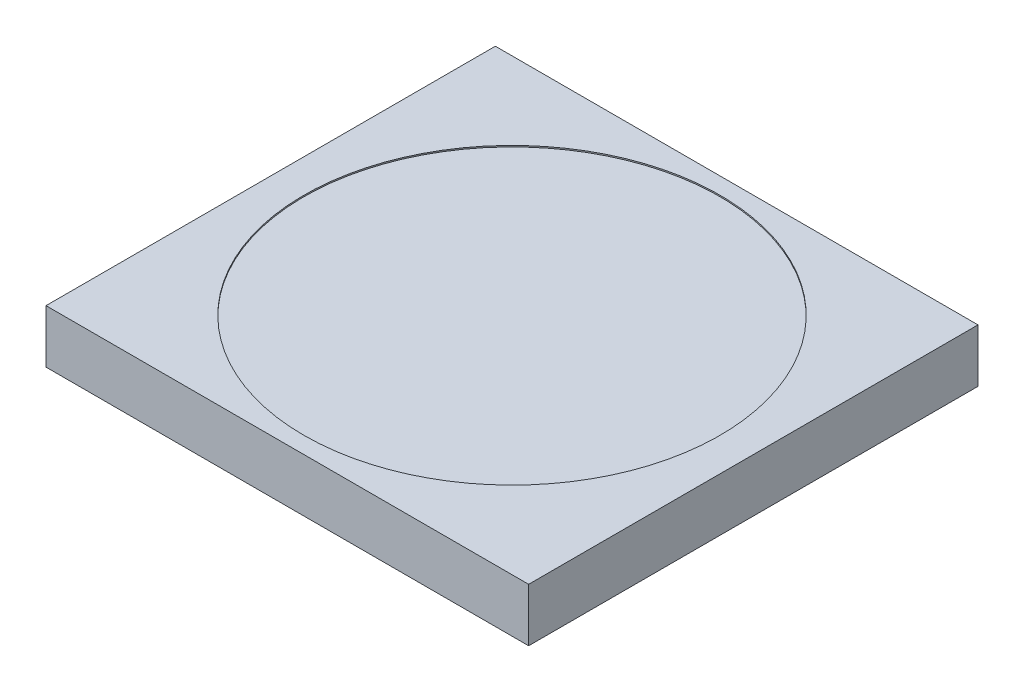
SolidWorks part; units mm, degrees
ref_plane "Front Plane" through (0, 0, 0) normal (0, 0, 1) x (1, 0, 0)
ref_plane "Top Plane" through (0, 0, 0) normal (0, 1, 0) x (1, 0, 0)
ref_plane "Right Plane" through (0, 0, 0) normal (1, 0, 0) x (0, 0, -1)
sketch "Sketch1" plane through (0, 0, 0) normal (0, 1, 0) x (1, 0, 0)
  line L1 (-145, 135) -> (145, 135)
  line L2 (-145, 135) -> (-145, -135)
  line L3 (-145, -135) -> (145, -135)
  line L4 (145, 135) -> (145, -135)
  line L5 (-145, 135) -> (145, -135) construction
  line L6 (-145, -135) -> (145, 135) construction
  point P0 (0, 0)
  dimension "D1" = 290
  dimension "D2" = 270
extrude "Boss-Extrude1" add sketch "Sketch1" along normal mid plane 32
sketch "Sketch2" plane through (0, 16, 0) normal (0, 1, 0) x (1, 0, 0)
  circle A0 centre (0, 0) radius 125
  dimension "D1" = 250
extrude "Cut-Extrude1" cut sketch "Sketch2" against normal blind 0.8
